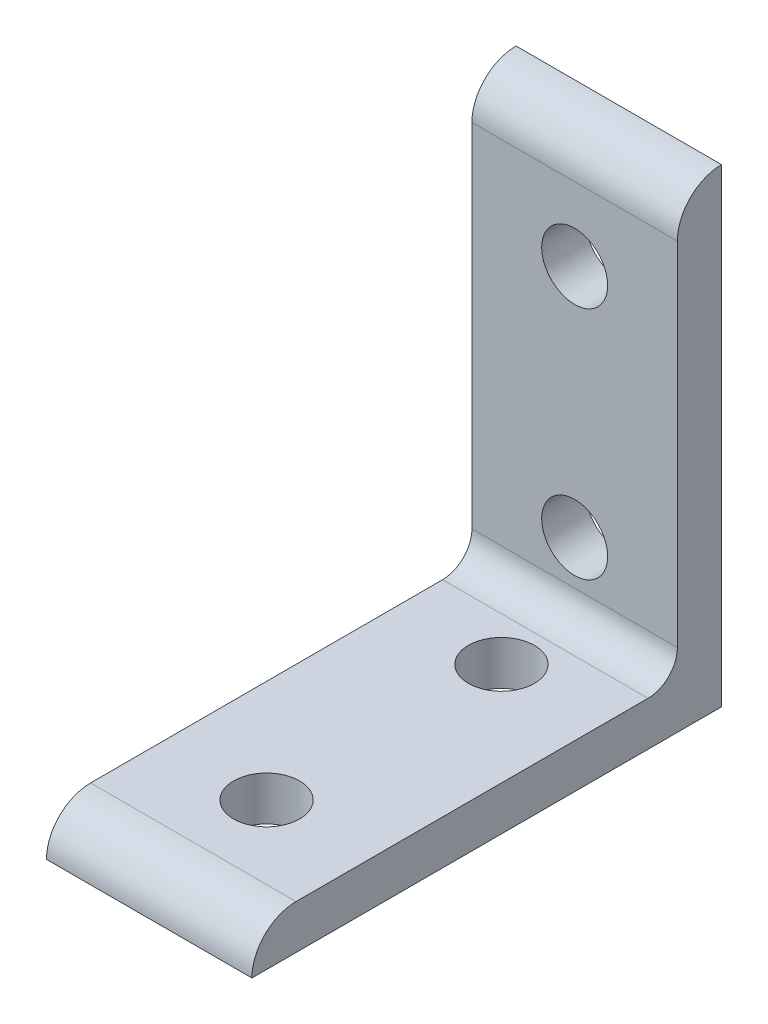
SolidWorks part; units mm, degrees
material "6105-T5 Aluminum"
ref_plane "Front Plane" through (0, 0, 0) normal (0, 0, 1) x (1, 0, 0)
ref_plane "Top Plane" through (0, 0, 0) normal (0, 1, 0) x (1, 0, 0)
ref_plane "Right Plane" through (0, 0, 0) normal (1, 0, 0) x (0, 0, -1)
ref_plane "Plane1" through (22.225, 0, 0) normal (1, 0, 0) x (0, 0, -1)
sketch "Sketch1" plane through (22.225, 0, 0) normal (1, 0, 0) x (0, 0, -1)
  line L0 (17.8256, 67.9225) -> (17.8256, 26.6729)
  line L1 (17.8256, 26.6729) -> (-23.424, 26.6729)
  line L2 (-28.1992, 21.8977) -> (22.6008, 21.8977)
  line L3 (22.6008, 21.8977) -> (22.6008, 72.6977)
  arc A0 (-23.424, 26.6729) -> (-28.1992, 21.8977) centre (-23.424, 21.8977) ccw
  arc A1 (22.6008, 72.6977) -> (17.8256, 67.9225) centre (22.6008, 67.9225) ccw
extrude "Boss-Extrude1" add sketch "Sketch1" against normal blind 22.225
hole_wizard "K (0.281) Diameter Hole1" positions "Sketch3" profile "Sketch2" hole size "K" standard "ANSI Inch" end condition through all
sketch "Sketch3" plane through (0, 0, -22.6008) normal (0, 0, -1) x (-1, 0, 0)
  point P0 (-11.1125, 59.9977)
  point P1 (-11.1125, 34.5977)
sketch "Sketch2" plane through (11.1125, 59.9977, -22.6008) normal (1, 0, 0) x (0, 1, 0)
  line L0 (0, 0) -> (0, 50.8)
  line L1 (0, 50.8) -> (3.5687, 50.8)
  line L2 (3.5687, 50.8) -> (3.5687, 0)
  line L5 (3.5687, 0) -> (0, 0)
  line L11 (0, -6.35) -> (0, 107.95) construction
  dimension "Thru Hole Dia." = 7.1374
  dimension "Thru Hole Depth" = 50.8
hole_wizard "K (0.281) Diameter Hole2" positions "Sketch5" profile "Sketch4" hole size "K" standard "ANSI Inch" end condition through all
sketch "Sketch5" plane through (0, 26.6729, 0) normal (0, 1, 0) x (1, 0, 0)
  point P0 (11.1125, 9.9008)
  point P1 (11.1125, -15.4992)
sketch "Sketch4" plane through (11.1125, 26.6729, -9.9008) normal (1, 0, 0) x (0, 0, 1)
  line L0 (0, 0) -> (0, 4.7752)
  line L1 (0, 4.7752) -> (3.5687, 4.7752)
  line L2 (3.5687, 4.7752) -> (3.5687, 0)
  line L5 (3.5687, 0) -> (0, 0)
  line L11 (0, -6.35) -> (0, 107.95) construction
  dimension "Thru Hole Dia." = 7.1374
  dimension "Thru Hole Depth" = 4.7752
fillet "Fillet1" radius 3.175 1 edges at (11.1125, 26.6729, -17.8256)
